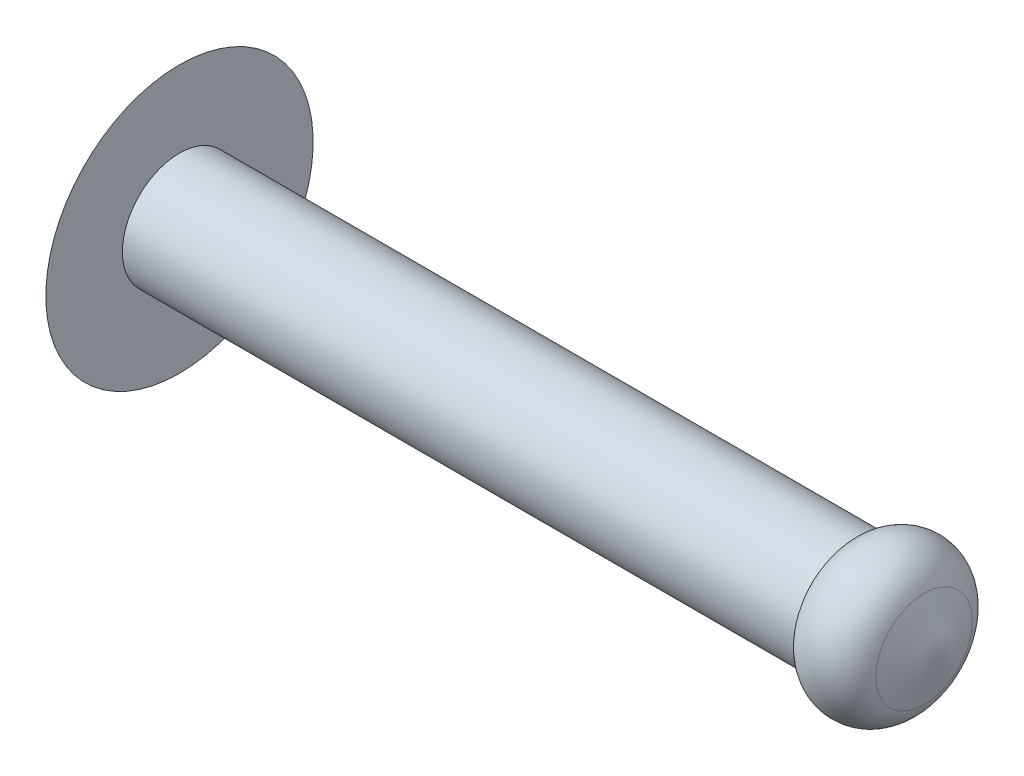
SolidWorks part; units mm, degrees
ref_plane "Alzado" through (0, 0, 0) normal (0, 0, 1) x (1, 0, 0)
ref_plane "Planta" through (0, 0, 0) normal (0, 1, 0) x (1, 0, 0)
ref_plane "Vista lateral" through (0, 0, 0) normal (1, 0, 0) x (0, 0, -1)
sketch "Croquis1" plane through (0, 0, 0) normal (0, 0, 1) x (1, 0, 0)
  line L0 (-15, 0) -> (15, 0) construction
  line L1 (15, 0) -> (14.35, 1.9)
  line L2 (-15, 2.25) -> (11.5, 2.25)
  line L3 (-15, 2.25) -> (-15, 5.2678)
  line L4 (-15, 0) -> (-16.5, 0) construction
  line L5 (15, 0) -> (-16.5, 0)
  arc A0 (14.35, 1.9) -> (11.5, 2.25) centre (12.8401, 1.3834) ccw
  arc A1 (-15, 5.2678) -> (-16.5, 0) centre (-6.5, 0) ccw
  point P4 (0, 0)
  dimension "D7" = 10
  dimension "D1" = 30
  dimension "D2" = 0.65
  dimension "D3" = 1.9
  dimension "D4" = 3.5
  dimension "D5" = 4.5
  dimension "D6" = 1.5
revolve "Revolución1" add sketch "Croquis1" angle 360 about L5
